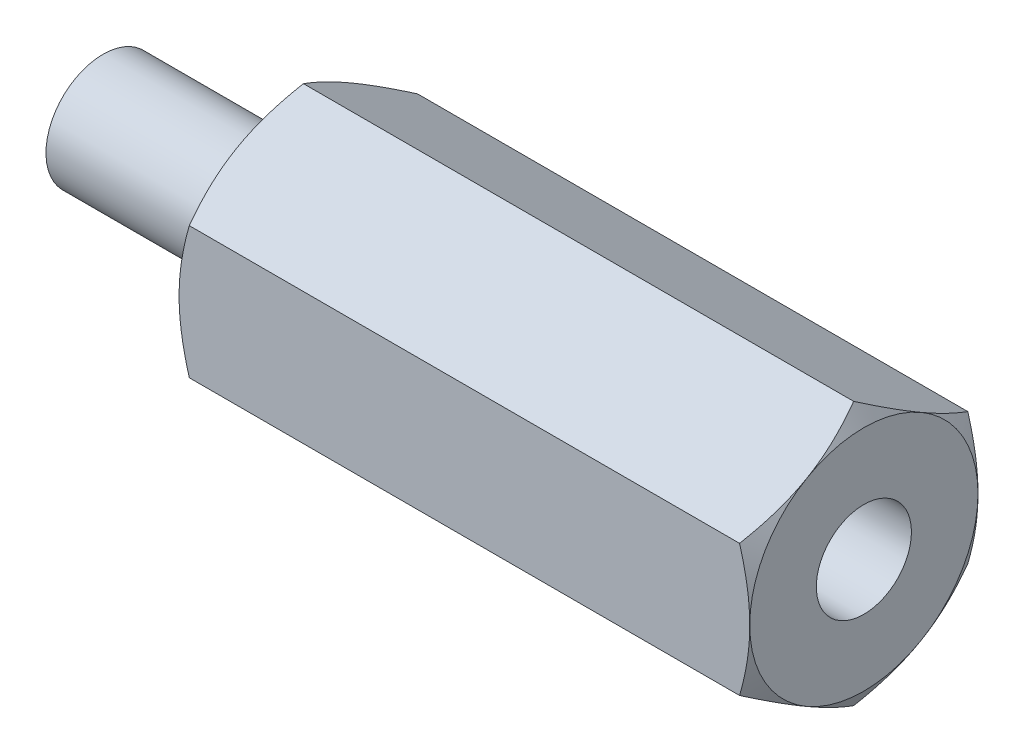
SolidWorks part; units mm, degrees
material "一般構造用鋼"
ref_plane "Front Plane" through (0, 0, 0) normal (0, 0, 1) x (1, 0, 0)
ref_plane "Top Plane" through (0, 0, 0) normal (0, 1, 0) x (1, 0, 0)
ref_plane "Right Plane" through (0, 0, 0) normal (1, 0, 0) x (0, 0, -1)
sketch "Sketch1" plane through (0, 0, 0) normal (1, 0, 0) x (0, 0, -1)
  line L1 (0, 3.4641) -> (-3, 1.7321)
  line L2 (-3, 1.7321) -> (-3, -1.7321)
  line L3 (-3, -1.7321) -> (0, -3.4641)
  line L4 (0, -3.4641) -> (3, -1.7321)
  line L5 (3, -1.7321) -> (3, 1.7321)
  line L6 (3, 1.7321) -> (0, 3.4641)
  circle A0 centre (0, 0) radius 3 construction
  dimension "B" = 6
  dimension "C" = 6.9282
extrude "Boss-Extrude1" add sketch "Sketch1" along normal blind 15
sketch "Sketch2" plane through (0, 0, 0) normal (0, 0, 1) x (1, 0, 0)
  line L0 (0, 0) -> (15, 0) construction
  line L1 (15, 1.7321) -> (15, -1.7321) construction
  line L2 (0.2679, 3.4641) -> (0, 3.4641)
  line L3 (0, 3.4641) -> (0, 3)
  line L4 (0, 3) -> (0.2679, 3.4641)
  line L5 (0, 1.7321) -> (0, 3.4641) construction
  line L6 (15, 3.4641) -> (0, 3.4641) construction
  line L8 (15, 3) -> (15, 3.4641)
  line L9 (15, 3.4641) -> (14.7321, 3.4641)
  line L10 (14.7321, 3.4641) -> (15, 3)
  line L11 (15, 3.4641) -> (15, 1.7321) construction
  dimension "D1" = 30
revolve "Cut-Revolve1" cut sketch "Sketch2" angle 360 about L0
sketch "Sketch3" plane through (0, 0, 0) normal (0, 0, 1) x (1, 0, 0)
  line L0 (0, 0) -> (-5, 0) construction
  line L1 (0, 0) -> (0, 1.5)
  line L2 (0, 3.4641) -> (0, 3) construction
  line L3 (-1.5, 1.5) -> (-1.5, 0) construction
  line L4 (0, 1.5) -> (-5, 1.5)
  line L5 (-5, 1.5) -> (-5, 0)
  line L6 (-5, 0) -> (0, 0)
  dimension "A" = 1.5
  dimension "M" = 3
  dimension "F" = 5
revolve "Revolve1" add sketch "Sketch3" angle 360 about L0
cosmetic thread "Cosmetic Thread1" parameters "D1"=3.5, "TD_s"=2.459
hole_wizard "Tapped Hole1" positions "Sketch5" profile "Sketch4" tap size "M3x0.5" standard "JIS"
sketch "Sketch5" plane through (15, 0, 0) normal (1, 0, 0) x (0, 0, -1)
  point P0 (0, 0)
sketch "Sketch4" plane through (15, 0, 0) normal (0, 1, 0) x (0, 0, -1)
  line L0 (0, 0) -> (0, 9.2511)
  line L1 (0, 9.2511) -> (1.25, 8.5)
  line L2 (1.25, 8.5) -> (1.25, 0)
  line L5 (1.25, 0) -> (0, 0)
  line L10 (0, 9.2511) -> (-1.25, 8.5) construction
  line L11 (0, 0) -> (0, 9.2511) construction
  dimension "Tap Drill Dia." = 2.5
  dimension "Tap Drill Depth" = 8.5
  dimension "Drill Angle" = 118
cosmetic thread "Hole Thread1" parameters "Nx2"=6, "N"=3
fillet "Fillet1" radius 0.5 1 edges at (0, 1.5, 0)
sketch "Sketch6" [suppressed] plane through (0, 0, 0) normal (0, 0, 1) x (1, 0, 0)
  line L0 (0, 0) -> (-5, 0) construction
  line L1 (-5, 1.5) -> (-5, -1.5) construction
  line L2 (0, 3.4641) -> (0, 1.7321) construction
  line L3 (-1.5, 3.4641) -> (0, 3.4641)
  line L4 (-1.5, 3.4641) -> (-1.5, 1.15)
  line L6 (0, 3.4641) -> (0, 1.15)
  line L7 (-1.5, 1.5) -> (-1.5, 0) construction
  line L8 (14.7321, 3.4641) -> (0.2679, 3.4641) construction
  line L9 (0, 1.15) -> (-1.5, 1.15)
  dimension "MC" = 2.4
revolve "Cut-Revolve2" [suppressed] cut sketch "Sketch6" angle 360 about L0
hole_wizard "Tapped Hole2" [suppressed] positions "Sketch10" profile "Sketch9" tap size "M3x0.5" standard "JIS"
sketch "Sketch10" [suppressed] plane through (15, 0, 0) normal (1, 0, 0) x (0, 0, -1)
  point P0 (0, 0)
sketch "Sketch9" [suppressed] plane through (15, 0, 0) normal (0, 1, 0) x (0, 0, -1)
  line L0 (0, 0) -> (0, 12.2511)
  line L1 (0, 12.2511) -> (1.25, 11.5)
  line L2 (1.25, 11.5) -> (1.25, 0)
  line L5 (1.25, 0) -> (0, 0)
  line L10 (0, 12.2511) -> (-1.25, 11.5) construction
  line L11 (0, 0) -> (0, 12.2511) construction
  dimension "Tap Drill Dia." = 2.5
  dimension "Tap Drill Depth" = 11.5
  dimension "Drill Angle" = 118
cosmetic thread "Hole Thread2" [suppressed] parameters "Nx3"=9, "ND"=3
equation "\"D1@Cosmetic Thread1\" = \"F@Sketch3\" - \"A@Sketch3\""
